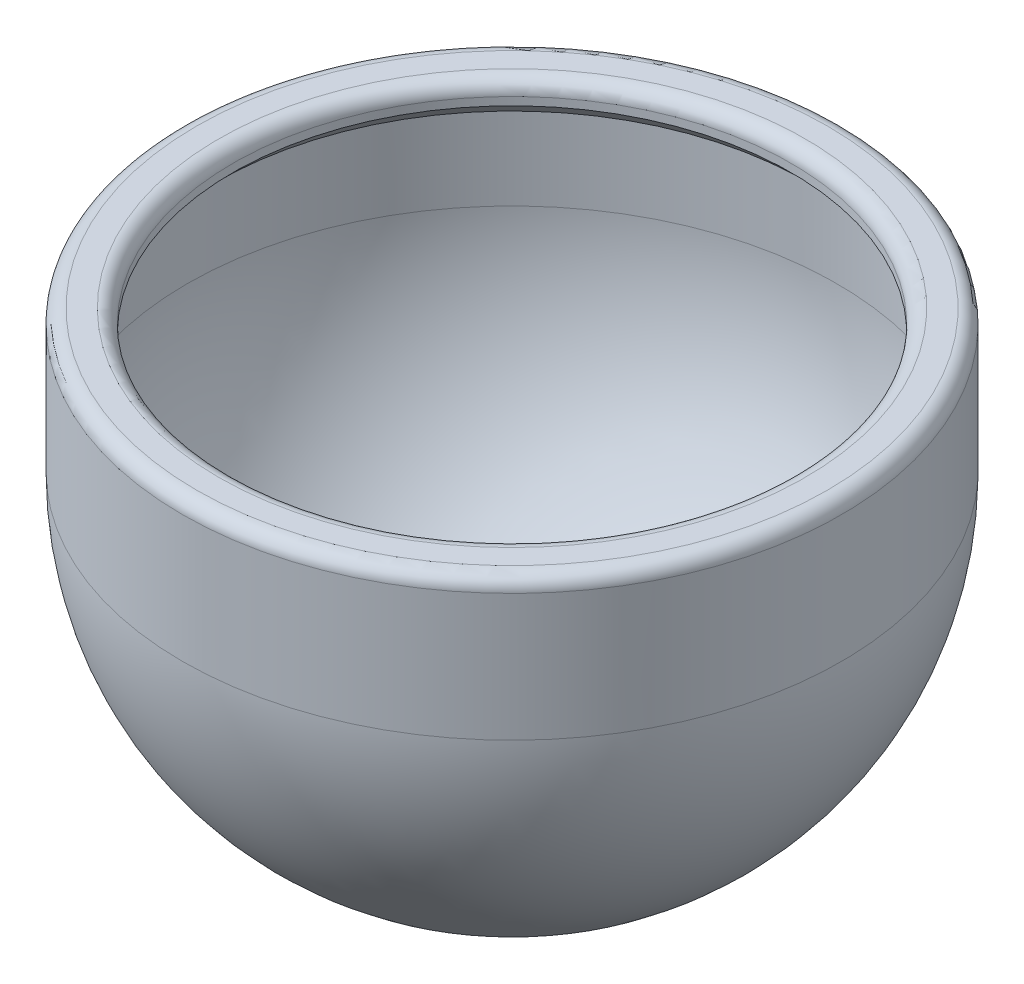
SolidWorks part; units mm, degrees
ref_plane "Front Plane" through (0, 0, 0) normal (0, 0, 1) x (1, 0, 0)
ref_plane "Top Plane" through (0, 0, 0) normal (0, 1, 0) x (1, 0, 0)
ref_plane "Right Plane" through (0, 0, 0) normal (1, 0, 0) x (0, 0, -1)
sketch "Sketch1" plane through (0, 0, 0) normal (0, 0, 1) x (1, 0, 0)
  line L0 (0, 64.2313) -> (0, -77.9951) construction
  line L2 (-70, 0) -> (-70, 27)
  line L3 (-67, 30) -> (-62.2929, 30)
  line L4 (0, -69) -> (0, -70)
  line L6 (-69, 0) -> (-69, 22)
  line L7 (-67, 29) -> (-63, 29)
  line L9 (-69, 23) -> (-69, 27)
  line L10 (-59.2929, 27) -> (-59.2929, 25.2929)
  line L11 (-59.2929, 27) -> (-70, 27)
  line L12 (-60, 26) -> (-70, 26)
  line L13 (-69, 23) -> (-63, 23)
  line L14 (-69, 22) -> (-62.5858, 22)
  line L15 (-76.0862, 22) -> (-49.8877, 22) construction
  line L16 (-60, 26) -> (-63, 23)
  line L17 (-76.0862, 23) -> (-49.8877, 23) construction
  line L18 (-59.2929, 25.2929) -> (-62.5858, 22)
  arc A0 (-70, 0) -> (0, -70) centre (0, 0) ccw
  arc A2 (-70, 27) -> (-67, 30) centre (-67, 27) cw
  arc A3 (-69, 0) -> (0, -69) centre (0, 0) ccw
  arc A4 (-67, 29) -> (-69, 27) centre (-67, 27) ccw
  arc A6 (-60, 26) -> (-63, 29) centre (-63, 26) ccw
  arc A7 (-59.2929, 27) -> (-62.2929, 30) centre (-62.2929, 27) ccw
  point P23 (-60.9393, 23.6464)
  dimension "D3" = 1
  dimension "D5" = 3
  dimension "D7" = 3
  dimension "D8" = 1
  dimension "D9" = 3
  dimension "D10" = 1
  dimension "D11" = 7
  dimension "D12" = 1
revolve "Revolve1" add sketch "Sketch1" angle 360 about L0
